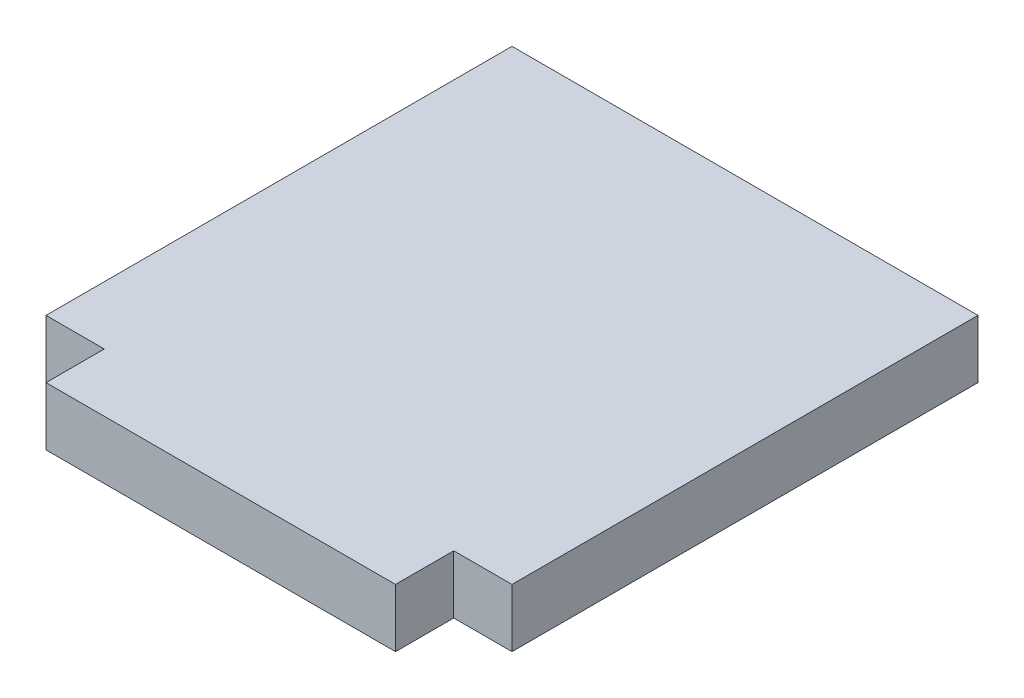
SolidWorks part; units mm, degrees
ref_plane "Alzado" through (0, 0, 0) normal (0, 0, 1) x (1, 0, 0)
ref_plane "Planta" through (0, 0, 0) normal (0, 1, 0) x (1, 0, 0)
ref_plane "Vista lateral" through (0, 0, 0) normal (1, 0, 0) x (0, 0, -1)
sketch "Croquis1" plane through (0, 0, 0) normal (0, 1, 0) x (1, 0, 0)
  line L0 (0, 0) -> (18, 0)
  line L1 (18, 0) -> (18, 3)
  line L2 (21, 3) -> (18, 3)
  line L3 (21, 3) -> (21, 27)
  line L4 (21, 27) -> (18, 27)
  line L7 (0, 27) -> (18, 27)
  line L9 (-3, 27) -> (0, 27)
  line L10 (-3, 3) -> (-3, 27)
  line L11 (0, 0) -> (0, 3)
  line L12 (18, 3) -> (18.0793, 3.0175)
  line L13 (0, 3) -> (-3, 3)
  point P13 (9, 30)
  dimension "D1" = 3
  dimension "D2" = 18
  dimension "D4" = 24
extrude "Saliente-Extruir1" add sketch "Croquis1" along normal blind 3
